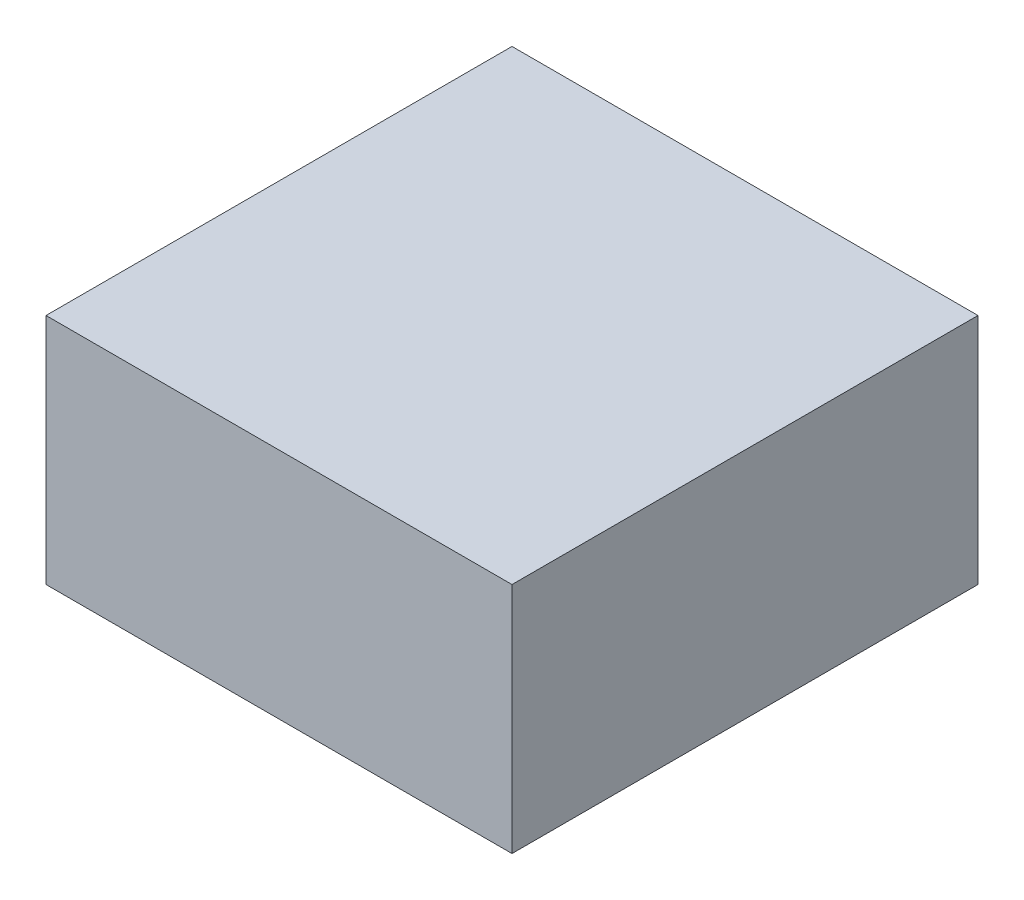
SolidWorks part; units mm, degrees
ref_plane "前视基准面" through (0, 0, 0) normal (0, 0, 1) x (1, 0, 0)
ref_plane "上视基准面" through (0, 0, 0) normal (0, 1, 0) x (1, 0, 0)
ref_plane "右视基准面" through (0, 0, 0) normal (1, 0, 0) x (0, 0, -1)
other "Configuration Table"
sketch "草图1" plane through (0, 0, 0) normal (0, 1, 0) x (1, 0, 0)
  line L1 (-15, -15) -> (15, -15)
  line L2 (-15, -15) -> (-15, 15)
  line L3 (-15, 15) -> (15, 15)
  line L4 (15, -15) -> (15, 15)
  line L5 (-15, -15) -> (15, 15) construction
  line L6 (-15, 15) -> (15, -15) construction
  point P0 (0, 0)
  dimension "D1" = 30
  dimension "D2" = 30
extrude "凸台-拉伸1" add sketch "草图1" along normal blind 15
